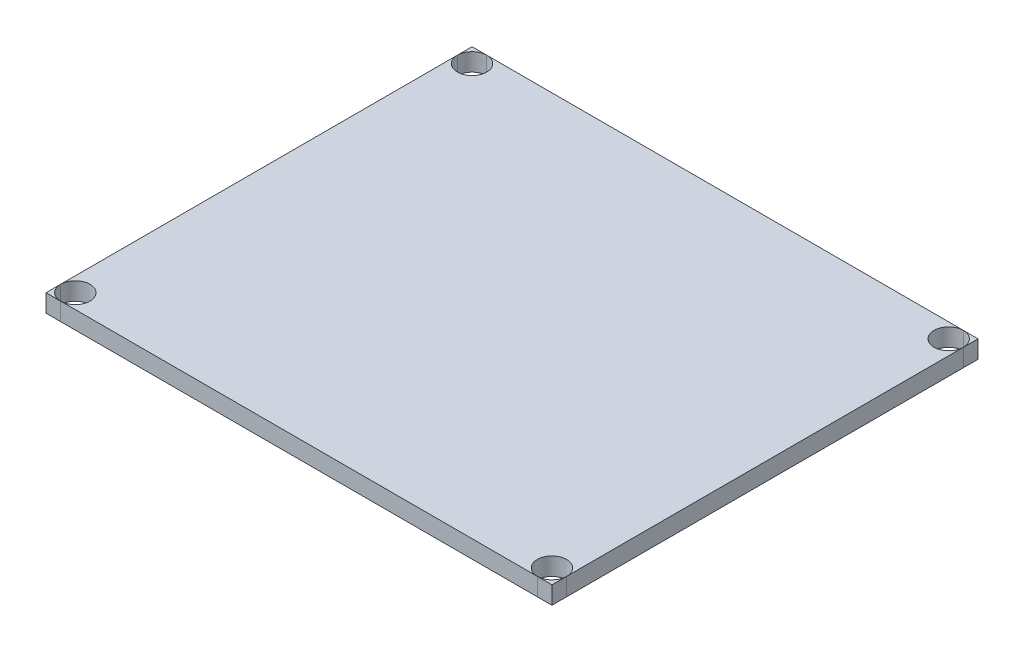
SolidWorks part; units mm, degrees
ref_plane "Front Plane" through (0, 0, 0) normal (0, 0, 1) x (1, 0, 0)
ref_plane "Top Plane" through (0, 0, 0) normal (0, 1, 0) x (1, 0, 0)
ref_plane "Right Plane" through (0, 0, 0) normal (1, 0, 0) x (0, 0, -1)
sketch "Sketch1" plane through (0, 0, 0) normal (0, 1, 0) x (1, 0, 0)
  line L1 (-28.5, 24) -> (28.5, 24)
  line L2 (-28.5, 24) -> (-28.5, -24)
  line L3 (-28.5, -24) -> (28.5, -24)
  line L4 (28.5, 24) -> (28.5, -24)
  line L5 (-28.5, 24) -> (28.5, -24) construction
  line L6 (-28.5, -24) -> (28.5, 24) construction
  line L7 (-26.85, 22.35) -> (26.85, 22.35) construction
  line L8 (-26.85, 22.35) -> (-26.85, -22.35) construction
  line L9 (-26.85, -22.35) -> (26.85, -22.35) construction
  line L10 (26.85, 22.35) -> (26.85, -22.35) construction
  line L11 (-26.85, 22.35) -> (26.85, -22.35) construction
  line L12 (-26.85, -22.35) -> (26.85, 22.35) construction
  circle A0 centre (-26.85, 22.35) radius 1.65
  circle A1 centre (26.85, 22.35) radius 1.65
  circle A2 centre (26.85, -22.35) radius 1.65
  circle A3 centre (-26.85, -22.35) radius 1.65
  point P0 (0, 0)
  point P6 (0, 0)
  dimension "D3" = 3.3
  dimension "D1" = 57
  dimension "D2" = 48
  dimension "D4" = 1.65
  dimension "D5" = 1.65
extrude "Boss-Extrude1" add sketch "Sketch1" along normal blind 2 contours A3 L3 A2 L4 A1 L1 A0 L2 | A3 L2 L3 | A2 L3 L4 | A1 L4 L1 | A0 L1 L2
